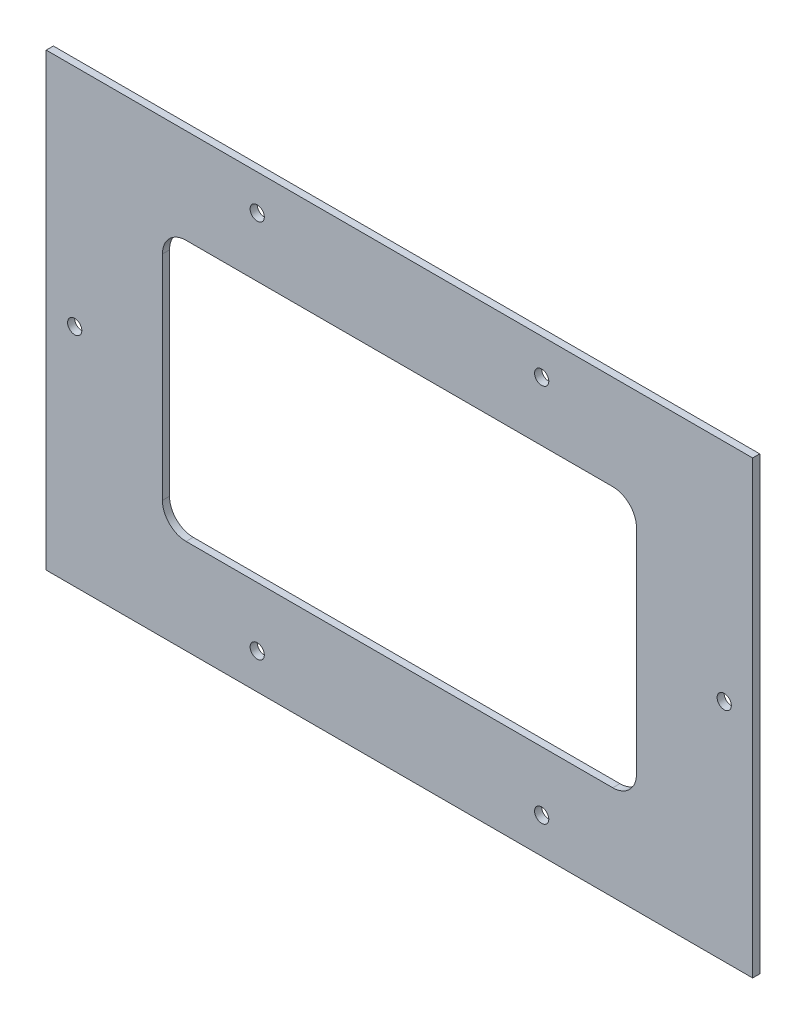
SolidWorks part; units mm, degrees
material "Alliage 1060"
ref_plane "Plan de face" through (0, 0, 0) normal (0, 0, 1) x (1, 0, 0)
ref_plane "Plan de dessus" through (0, 0, 0) normal (0, 1, 0) x (1, 0, 0)
ref_plane "Plan de droite" through (0, 0, 0) normal (1, 0, 0) x (0, 0, -1)
sketch "Esquisse1" plane through (0, 0, 0) normal (0, 0, 1) x (1, 0, 0)
  line L0 (0, 80) -> (0, 0) construction
  line L1 (-74.5, 165) -> (74.5, 165)
  line L2 (-74.5, 165) -> (-74.5, 0)
  line L3 (-74.5, 0) -> (74.5, 0)
  line L4 (74.5, 165) -> (74.5, 0)
  line L5 (-50, 135) -> (50, 135)
  line L6 (-50, 135) -> (-50, 80)
  line L7 (-50, 80) -> (50, 80)
  line L8 (50, 135) -> (50, 80)
  dimension "D1" = 165
  dimension "D2" = 149
  dimension "D3" = 55
  dimension "D4" = 100
  dimension "D5" = 80
extrude "Boss.-Extru.1" add sketch "Esquisse1" along normal blind 1.5
fillet "Congé1" radius 5 4 edges at (50, 80, 0.75) (50, 135, 0.75) (-50, 135, 0.75) (-50, 80, 0.75)
sketch "Esquisse2" plane through (0, 0, 1.5) normal (0, 0, 1) x (1, 0, 0)
  line L0 (-50, 107.5) -> (0, 107.5) construction
  line L1 (-50, 130) -> (-50, 85) construction
  line L2 (0, 107.5) -> (0, 135) construction
  line L3 (45, 135) -> (-45, 135) construction
  line L4 (-74.5, 82.5) -> (74.5, 82.5) construction
  line L5 (-74.5, 165) -> (-74.5, 0) construction
  line L6 (74.5, 0) -> (74.5, 165) construction
  line L7 (74.5, 165) -> (-74.5, 165) construction
  circle A0 centre (-30, 147.5) radius 1.5
  circle A1 centre (-30, 67.5) radius 1.5
  circle A2 centre (30, 67.5) radius 1.5
  circle A3 centre (30, 147.5) radius 1.5
  circle A4 centre (-55, 160) radius 1.5
  circle A5 centre (-55, 5) radius 1.5
  circle A6 centre (55, 5) radius 1.5
  circle A7 centre (55, 160) radius 1.5
  dimension "D1" = 80
  dimension "D2" = 3
  dimension "D3" = 60
  dimension "D4" = 5
  dimension "D5" = 110
  dimension "D6" = 155
extrude "Enlèv. mat.-Extru.1" cut sketch "Esquisse2" against normal through all
sketch "Esquisse3" plane through (0, 0, 1.5) normal (0, 0, 1) x (1, 0, 0)
  line L0 (74.5, 0) -> (74.5, 165) construction
  line L1 (-74.5, 165) -> (74.5, 165)
  line L2 (-74.5, 165) -> (-74.5, 155)
  line L3 (-74.5, 155) -> (74.5, 155)
  line L4 (74.5, 165) -> (74.5, 155)
  line L5 (-74.5, 165) -> (-74.5, 0) construction
  line L6 (74.5, 0) -> (-74.5, 0)
  line L7 (74.5, 0) -> (74.5, 60)
  line L8 (74.5, 60) -> (-74.5, 60)
  line L9 (-74.5, 0) -> (-74.5, 60)
  line L10 (-50, 107.5) -> (50, 107.5) construction
  line L11 (-50, 130) -> (-50, 85) construction
  line L12 (50, 85) -> (50, 130) construction
  line L13 (0, -0.825) -> (0, 0.825) construction
  circle A0 centre (-30, 147.5) radius 1.5 construction
  circle A1 centre (-68.5, 107.5) radius 1.5
  circle A2 centre (68.5, 107.5) radius 1.5
  point P28 (0, 0)
  dimension "D1" = 7.5
  dimension "D3" = 6
  dimension "D4" = 3
  dimension "D2" = 95
extrude "Enlèv. mat.-Extru.2" cut sketch "Esquisse3" against normal through all
